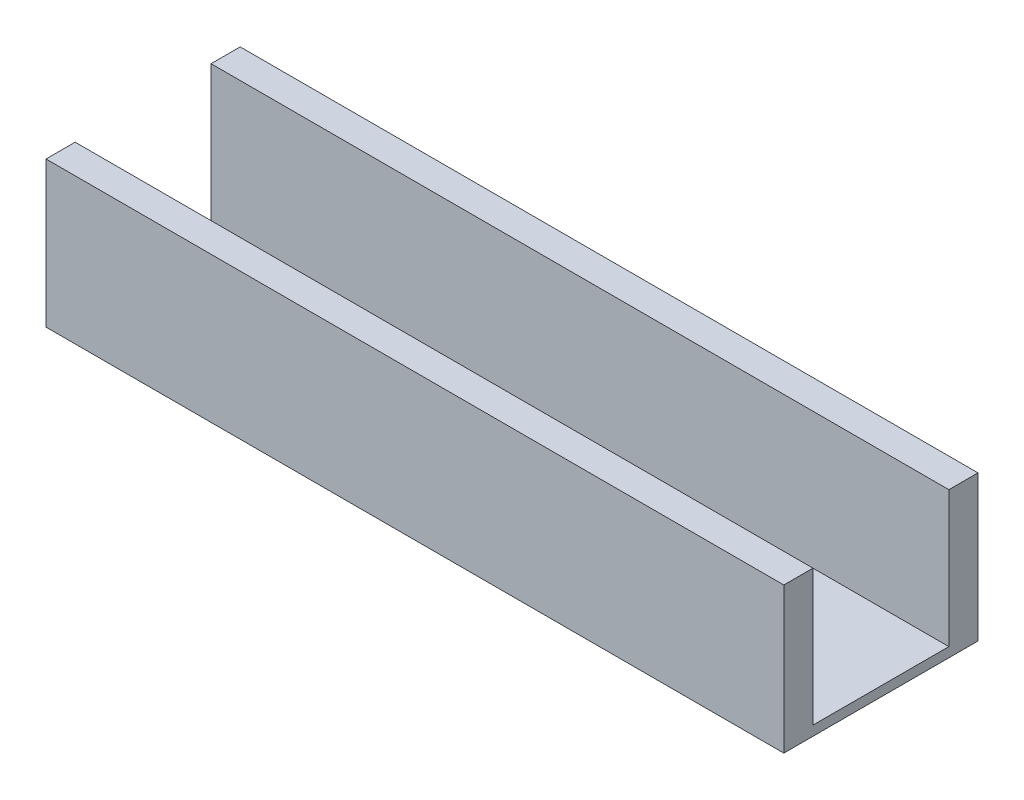
SolidWorks part; units mm, degrees
ref_plane "Front Plane" through (0, 0, 0) normal (0, 0, 1) x (1, 0, 0)
ref_plane "Top Plane" through (0, 0, 0) normal (0, 1, 0) x (1, 0, 0)
ref_plane "Right Plane" through (0, 0, 0) normal (1, 0, 0) x (0, 0, -1)
sketch "Acrylic Sheet" plane through (0, 0, 0) normal (0, 1, 0) x (1, 0, 0)
  line L0 (0, 0) -> (0, 127)
  line L1 (0, 127) -> (482.6, 127)
  line L2 (482.6, 127) -> (482.6, 0)
  line L3 (482.6, 0) -> (0, 0)
  dimension "D1" = 127
  dimension "D2" = 482.6
extrude "Boss-Extrude1" add sketch "Acrylic Sheet" along normal blind 6.35
sketch "Sketch2" plane through (0, 6.35, 0) normal (0, 1, 0) x (1, 0, 0)
  line L0 (482.6, 0) -> (482.6, 127) construction
  line L1 (0, 0) -> (482.6, 0)
  line L2 (0, 0) -> (0, 19.05)
  line L3 (0, 19.05) -> (482.6, 19.05)
  line L4 (482.6, 0) -> (482.6, 19.05)
  line L7 (0, 107.95) -> (482.6, 107.95)
  line L8 (482.6, 127) -> (482.6, 107.95)
  line L9 (0, 127) -> (482.6, 127)
  line L10 (0, 127) -> (0, 107.95)
  dimension "D1" = 19.05
  dimension "D2" = 88.9
extrude "Boss-Extrude2" add sketch "Sketch2" along normal blind 88.9
